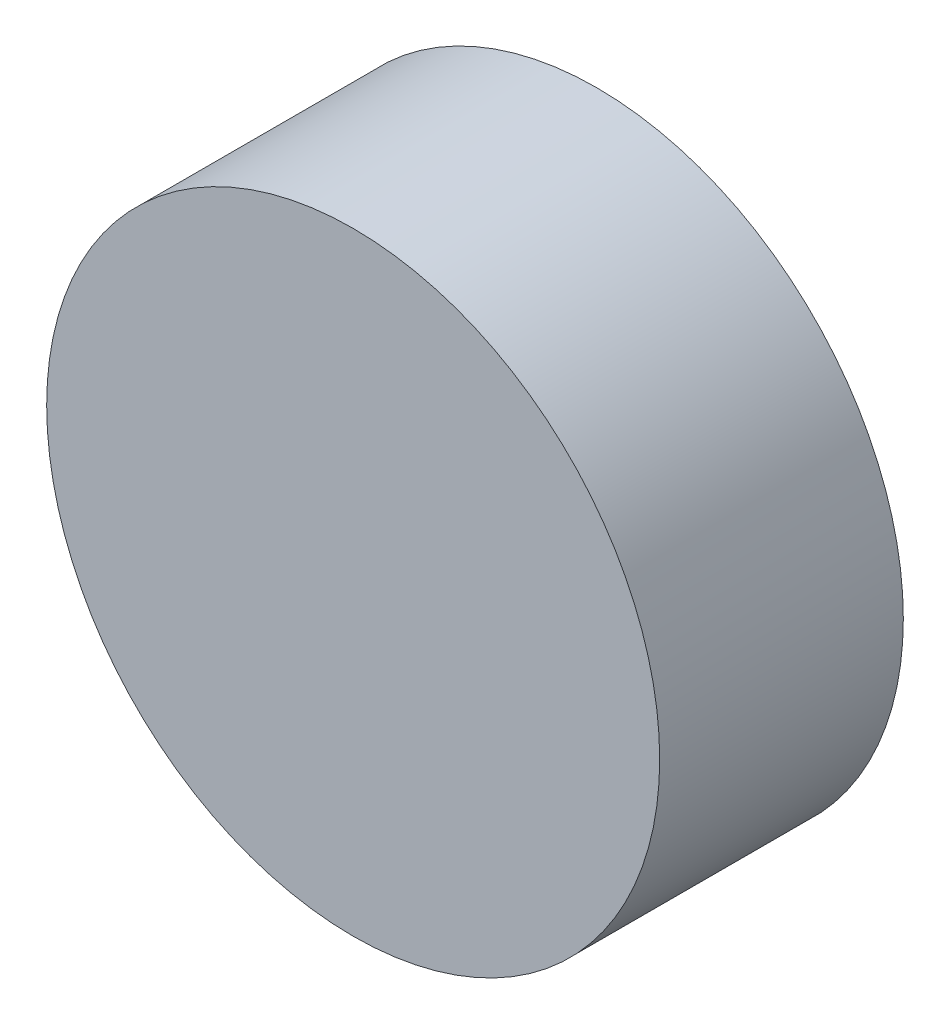
SolidWorks part; units mm, degrees
ref_plane "Front Plane" through (0, 0, 0) normal (0, 0, 1) x (1, 0, 0)
ref_plane "Top Plane" through (0, 0, 0) normal (0, 1, 0) x (1, 0, 0)
ref_plane "Right Plane" through (0, 0, 0) normal (1, 0, 0) x (0, 0, -1)
sketch "Sketch1" plane through (0, 0, 0) normal (0, 0, 1) x (1, 0, 0)
  circle A0 centre (0, 0) radius 29
  dimension "D1" = 58
extrude "Boss-Extrude1" add sketch "Sketch1" along normal blind 23.0502
